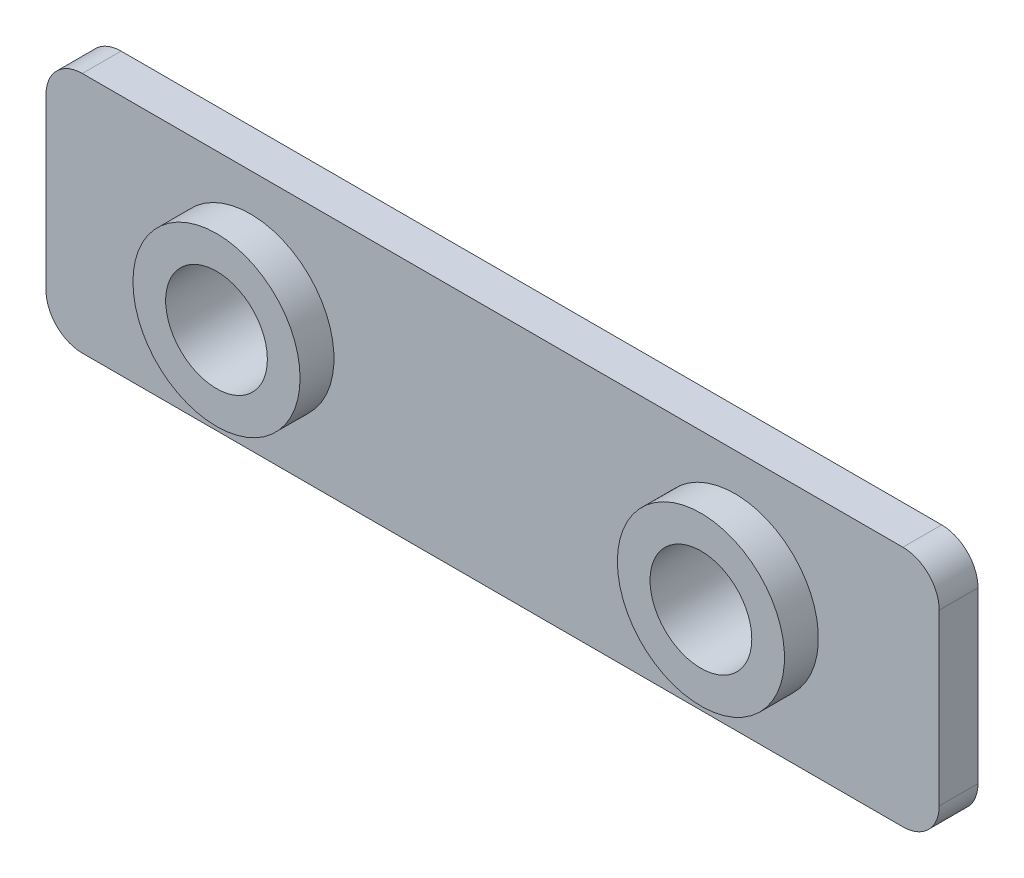
SolidWorks part; units mm, degrees
material "Plain Carbon Steel"
ref_plane "Front Plane" through (0, 0, 0) normal (0, 0, 1) x (1, 0, 0)
ref_plane "Top Plane" through (0, 0, 0) normal (0, 1, 0) x (1, 0, 0)
ref_plane "Right Plane" through (0, 0, 0) normal (1, 0, 0) x (0, 0, -1)
sketch "Sketch1" plane through (0, 0, 0) normal (0, 0, 1) x (1, 0, 0)
  line L0 (-18.44, -5) -> (18.44, 5) construction
  line L1 (-16.94, -5) -> (16.94, -5)
  line L2 (-18.44, -3.5) -> (-18.44, 3.5)
  line L3 (-16.94, 5) -> (16.94, 5)
  line L4 (18.44, -3.5) -> (18.44, 3.5)
  line L5 (18.44, 5) -> (18.44, -5) construction
  line L6 (18.44, -5) -> (-18.44, 5) construction
  arc A0 (16.94, 5) -> (18.44, 3.5) centre (16.94, 3.5) cw
  arc A1 (16.94, -5) -> (18.44, -3.5) centre (16.94, -3.5) ccw
  arc A2 (-16.94, -5) -> (-18.44, -3.5) centre (-16.94, -3.5) cw
  arc A3 (-18.44, 3.5) -> (-16.94, 5) centre (-16.94, 3.5) cw
  point P9 (18.44, -5)
  point P12 (-18.44, -5)
  point P15 (-18.44, 5)
  dimension "D3" = 1.5
  dimension "D1" = 36.88
  dimension "D2" = 10
extrude "Boss-Extrude1" add sketch "Sketch1" along normal blind 1.6
sketch "Sketch2" plane through (0, 0, 1.6) normal (0, 0, 1) x (1, 0, 0)
  line L0 (-18.44, 0) -> (0, 0) construction
  line L1 (-18.44, 3.5) -> (-18.44, -3.5) construction
  line L2 (0, 0) -> (0, 5) construction
  line L3 (16.94, 5) -> (-16.94, 5) construction
  circle A0 centre (-10, 0) radius 3.45
  circle A1 centre (10, 0) radius 3.45
  dimension "D2" = 6.9
  dimension "D1" = 20
extrude "Boss-Extrude2" add sketch "Sketch2" along normal blind 1.4
hole_wizard "M5x0.8 Tapped Hole1" positions "Sketch4" profile "Sketch3" tap size "M5x0.8" standard "ANSI Metric" end condition through all
sketch "Sketch4" plane through (0, 0, 3) normal (0, 0, 1) x (1, 0, 0)
  point P0 (-10, 0)
  point P3 (10, 0)
sketch "Sketch3" plane through (-10, 0, 3) normal (1, 0, 0) x (0, -1, 0)
  line L0 (0, 0) -> (0, 3)
  line L1 (0, 3) -> (2.1, 3)
  line L2 (2.1, 3) -> (2.1, 0)
  line L5 (2.1, 0) -> (0, 0)
  line L11 (0, -6.35) -> (0, 107.95) construction
  dimension "Thread Major Dia." = 4.2
  dimension "Thru Tap Drill Depth" = 3
